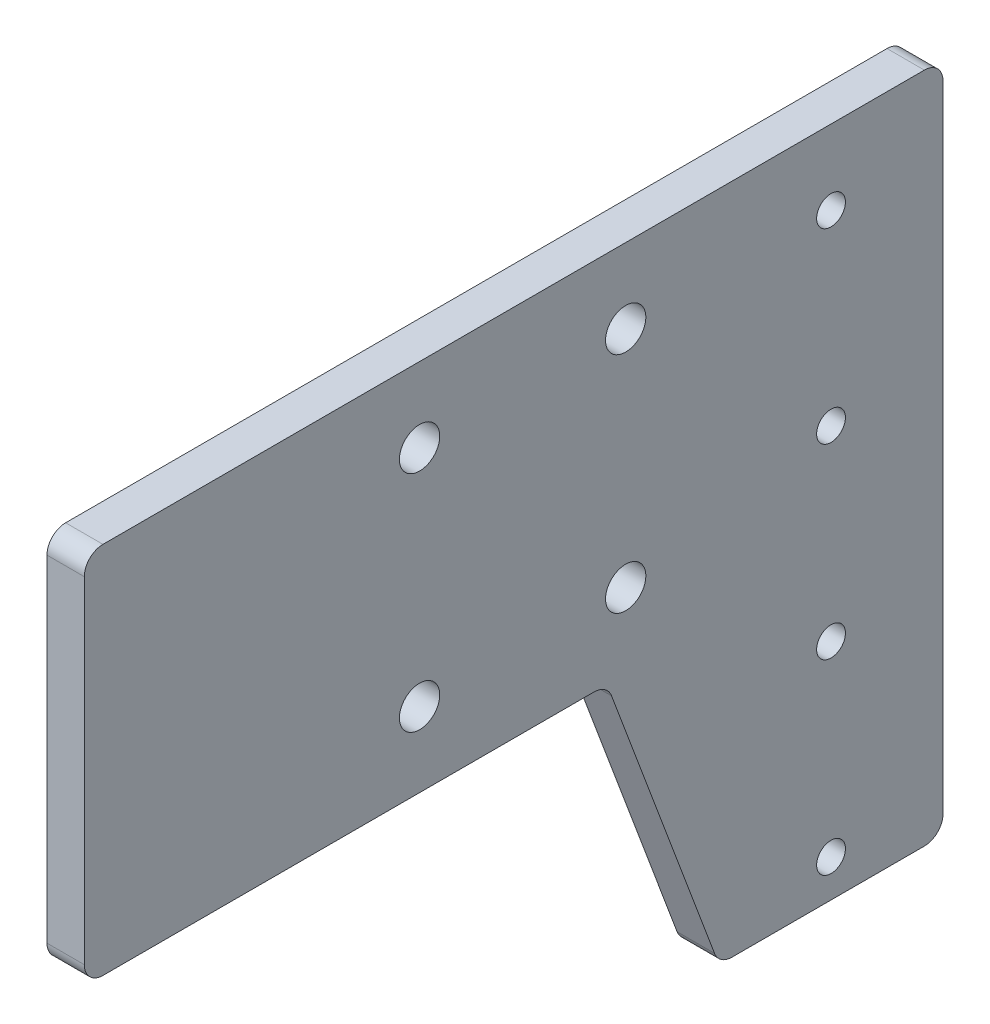
SolidWorks part; units mm, degrees
material "6061 Alloy"
ref_plane "Front Plane" through (0, 0, 0) normal (0, 0, 1) x (1, 0, 0)
ref_plane "Top Plane" through (0, 0, 0) normal (0, 1, 0) x (1, 0, 0)
ref_plane "Right Plane" through (0, 0, 0) normal (1, 0, 0) x (0, 0, -1)
sketch "Sketch1" plane through (0, 0, 0) normal (1, 0, 0) x (0, 0, -1)
  line L0 (0, 0) -> (-38.1, 0)
  line L1 (-38.1, 0) -> (-57.15, 50.8)
  line L2 (-57.15, 50.8) -> (-146.05, 50.8)
  line L3 (-146.05, 50.8) -> (-146.05, 114.3)
  line L4 (-146.05, 114.3) -> (0, 114.3)
  line L5 (0, 114.3) -> (0, 0)
  circle A0 centre (-19.05, 101.6) radius 2.4511
  circle A1 centre (-19.05, 69.85) radius 2.4511
  circle A2 centre (-19.05, 38.1) radius 2.4511
  circle A3 centre (-19.05, 6.35) radius 2.4511
  circle A4 centre (-53.975, 101.6) radius 3.429
  circle A5 centre (-89.027, 101.6) radius 3.429
  circle A6 centre (-89.027, 63.5) radius 3.429
  circle A7 centre (-53.975, 63.5) radius 3.429
  dimension "D6" = 4.9022
  dimension "D10" = 6.858
  dimension "D11" = 53.975
  dimension "D1" = 146.05
  dimension "D2" = 38.1
  dimension "D3" = 63.5
  dimension "D4" = 114.3
  dimension "D5" = 88.9
  dimension "D7" = 19.05
  dimension "D8" = 12.7
  dimension "D12" = 12.7
  dimension "D9" = 4
  dimension "D13" = 2
  dimension "D14" = 2
extrude "Boss-Extrude1" add sketch "Sketch1" along normal blind 6.35
fillet "Fillet1" radius 3.175 6 edges at (3.175, 114.3, 0) (3.175, 0, 0) (3.175, 50.8, 57.15) (3.175, 0, 38.1) (3.175, 50.8, 146.05) (3.175, 114.3, 146.05)
